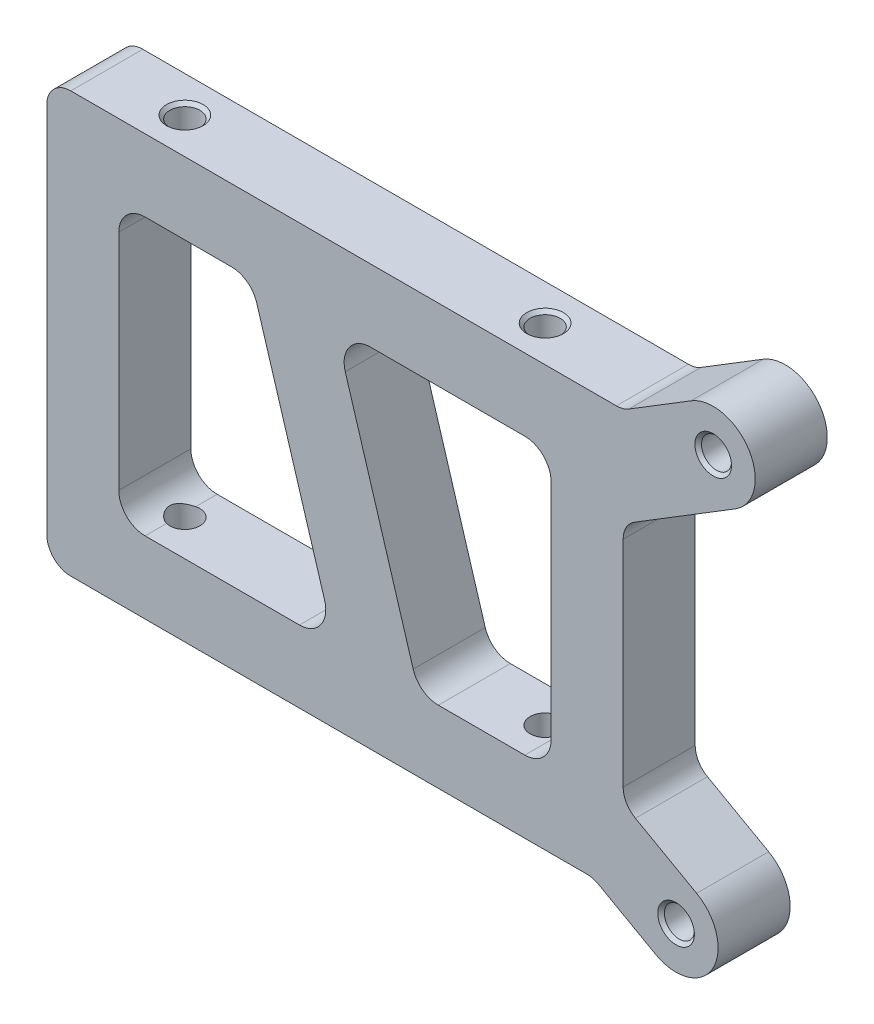
SolidWorks part; units mm, degrees
material "6061 合金"
ref_plane "前视基准面" through (0, 0, 0) normal (0, 0, 1) x (1, 0, 0)
ref_plane "上视基准面" through (0, 0, 0) normal (0, 1, 0) x (1, 0, 0)
ref_plane "右视基准面" through (0, 0, 0) normal (1, 0, 0) x (0, 0, -1)
sketch "草图1" plane through (0, 0, 0) normal (0, 0, 1) x (1, 0, 0)
  line L0 (-30.5148, 27.4468) -> (-24.8584, 8.826)
  line L1 (0, 0) -> (-46, 0)
  line L2 (0, 0) -> (0, 35)
  line L3 (0, 35) -> (-46, 35)
  line L4 (-48, 2) -> (-48, 33)
  line L5 (-39.8104, 29) -> (-32.6099, 29)
  line L6 (-42, 26.8104) -> (-42, 8.1896)
  line L7 (-39.8104, 6) -> (-26.9535, 6)
  line L8 (-6, 26.8104) -> (-6, 8.1896)
  line L9 (-23.1416, 26.174) -> (-17.4852, 7.5532)
  line L10 (-21.0465, 29) -> (-8.1896, 29)
  line L11 (-15.3901, 6) -> (-8.1896, 6)
  arc A0 (-46, 0) -> (-48, 2) centre (-46, 2) cw
  arc A1 (-48, 33) -> (-46, 35) centre (-46, 33) cw
  arc A2 (-6, 26.8104) -> (-8.1896, 29) centre (-8.1896, 26.8104) ccw
  arc A3 (-6, 8.1896) -> (-8.1896, 6) centre (-8.1896, 8.1896) cw
  arc A4 (-15.3901, 6) -> (-17.4852, 7.5532) centre (-15.3901, 8.1896) cw
  arc A5 (-21.0465, 29) -> (-23.1416, 26.174) centre (-21.0465, 26.8104) ccw
  arc A6 (-30.5148, 27.4468) -> (-32.6099, 29) centre (-32.6099, 26.8104) ccw
  arc A7 (-24.8584, 8.826) -> (-26.9535, 6) centre (-26.9535, 8.1896) cw
  arc A8 (-39.8104, 6) -> (-42, 8.1896) centre (-39.8104, 8.1896) cw
  arc A9 (-42, 26.8104) -> (-39.8104, 29) centre (-39.8104, 26.8104) cw
  point P17 (-24, 6)
  point P18 (-24, 6)
  point P25 (-17.0134, 6)
  dimension "D3" = 2
  dimension "D8" = 2.1896
  dimension "D1" = 35
  dimension "D2" = 48
  dimension "D4" = 6
  dimension "D5" = 6
  dimension "D6" = 6
  dimension "D7" = 6
extrude "凸台-拉伸1" add sketch "草图1" along normal blind 6
sketch "草图3" plane through (0, 0, 6) normal (0, 0, 1) x (1, 0, 0)
  line L0 (-42, 26.8104) -> (-42, 8.1896) construction
  line L1 (-15.3901, 6) -> (-8.1896, 6) construction
  line L2 (5.6679, 38.4822) -> (0.4817, 35.2959)
  line L3 (-0.5653, 35) -> (-3.3938, 35)
  line L4 (0, 35) -> (-46, 35) construction
  line L5 (-3.3938, 35) -> (-3.3938, 0)
  line L6 (-46, 0) -> (0, 0) construction
  line L7 (7.5, 35.5) -> (4.406, 0.1351) construction
  line L8 (9.3321, 32.5178) -> (0.9531, 27.37)
  line L9 (0, 0) -> (0, 35) construction
  line L10 (0, 25.6659) -> (0, 7.7929)
  line L11 (1.021, 6.0489) -> (6.1192, 3.1871)
  line L12 (2.6928, -2.917) -> (-2.0477, -0.256)
  line L13 (-3.0267, 0) -> (-3.3938, 0)
  arc A0 (9.3321, 32.5178) -> (5.6679, 38.4822) centre (7.5, 35.5) ccw
  arc A1 (2.6928, -2.917) -> (6.1192, 3.1871) centre (4.406, 0.1351) ccw
  arc A2 (0.4817, 35.2959) -> (-0.5653, 35) centre (-0.5653, 37) cw
  arc A3 (0, 25.6659) -> (0.9531, 27.37) centre (2, 25.6659) cw
  arc A4 (1.021, 6.0489) -> (0, 7.7929) centre (2, 7.7929) cw
  arc A5 (-2.0477, -0.256) -> (-3.0267, 0) centre (-3.0267, -2) ccw
  point P0 (7.5, 35.5)
  point P26 (-2.5037, 0)
  point P29 (0, 35)
  point P32 (0, 26.7845)
  point P35 (0, 6.622)
  point P38 (-2.5037, 0)
  dimension "D3" = 7
  dimension "D6" = 2
  dimension "D1" = 49.5
  dimension "D2" = 29.5
  dimension "D4" = 5
  dimension "D5" = 35.5
extrude "凸台-拉伸2" add sketch "草图3" against normal blind 6
hole_wizard "M3 螺纹孔1" positions "草图4" profile "草图5" tap size "M3" standard "GB" end condition through all
sketch "草图4" plane through (0, 0, 6) normal (0, 0, 1) x (1, 0, 0)
  arc A0 (2.6928, -2.917) -> (6.1192, 3.1871) centre (4.406, 0.1351) ccw construction
  arc A1 (9.3321, 32.5178) -> (5.6679, 38.4822) centre (7.5, 35.5) ccw construction
  point P0 (7.5, 35.5)
  point P2 (4.406, 0.1351)
  point P5 (0, 0)
  point P9 (0, 0)
sketch "草图5" plane through (7.5, 35.5, 6) normal (1, 0, 0) x (0, -1, 0)
  line L0 (0, 0) -> (0, 6)
  line L1 (0, 6) -> (1.25, 6)
  line L2 (1.25, 6) -> (1.25, 0.275)
  line L3 (1.25, 0.275) -> (1.525, 0)
  line L5 (1.525, 0) -> (0, 0)
  line L6 (-1.25, 0.275) -> (-1.525, 0) construction
  line L11 (0, -6.35) -> (0, 107.95) construction
  dimension "通孔螺纹孔钻头直径" = 2.5
  dimension "通孔螺纹孔钻头深度" = 6
  dimension "近端锥形沉头孔直径" = 3.05
  dimension "近端锥形沉头孔角度" = 90
cosmetic thread "孔螺蚊线1" parameters "D2"=3
cosmetic thread "孔螺蚊线2" parameters "D2"=3
sketch "草图6" plane through (0, 35, 0) normal (0, 1, 0) x (1, 0, 0)
  line L0 (-48, -3) -> (11, -3) construction
  line L1 (-48, -6) -> (-48, 0) construction
  line L2 (11, -6) -> (11, 0) construction
  point P6 (-39.5, -3)
  point P7 (-9.5, -3)
  dimension "D1" = 30
  dimension "D2" = 8.5
hole_wizard "M3 螺纹孔2" positions "草图7" profile "草图8" tap size "M3" standard "GB" end condition through all
sketch "草图7" plane through (0, 35, 0) normal (0, 1, 0) x (1, 0, 0)
  point P0 (-39.5, -3)
  point P3 (-9.5, -3)
sketch "草图8" plane through (-39.5, 35, 3) normal (1, 0, 0) x (0, 0, 1)
  line L0 (0, 0) -> (0, 38.3649)
  line L1 (0, 38.3649) -> (1.25, 38.3649)
  line L2 (1.25, 38.3649) -> (1.25, 0.275)
  line L3 (1.25, 0.275) -> (1.525, 0)
  line L5 (1.525, 0) -> (0, 0)
  line L6 (-1.25, 0.275) -> (-1.525, 0) construction
  line L11 (0, -6.35) -> (0, 107.95) construction
  dimension "通孔螺纹孔钻头直径" = 2.5
  dimension "通孔螺纹孔钻头深度" = 38.3649
  dimension "近端锥形沉头孔直径" = 3.05
  dimension "近端锥形沉头孔角度" = 90
cosmetic thread "孔螺蚊线3" parameters "D2"=3
cosmetic thread "孔螺蚊线4" parameters "D2"=3
